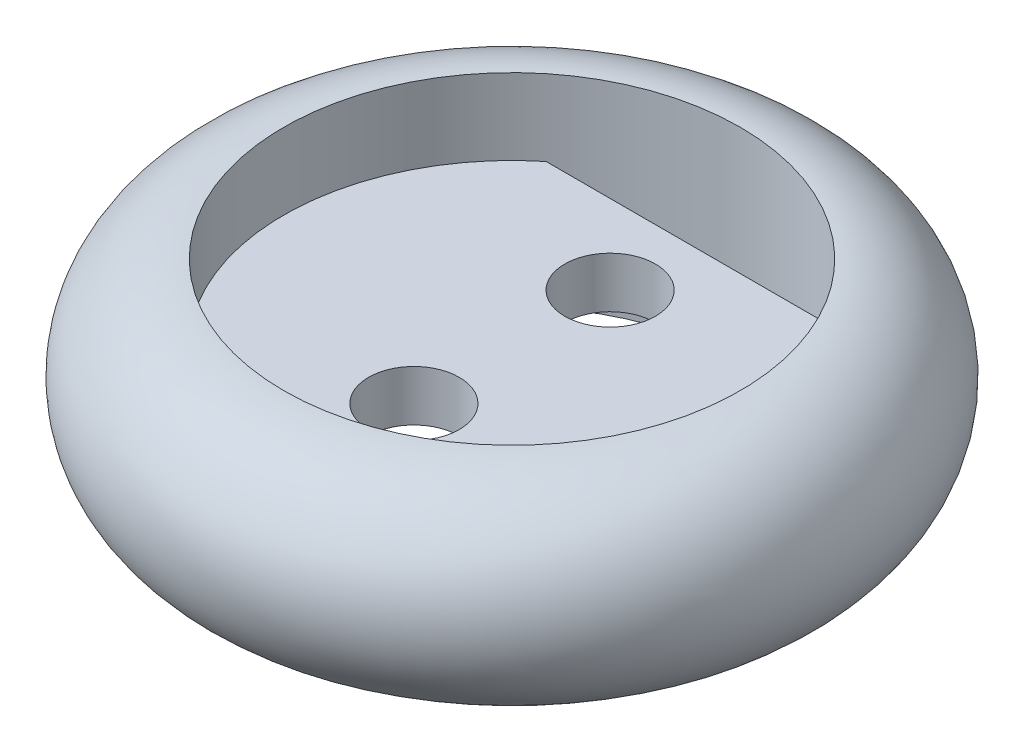
SolidWorks part; units mm, degrees
ref_plane "前视基准面" through (0, 0, 0) normal (0, 0, 1) x (1, 0, 0)
ref_plane "上视基准面" through (0, 0, 0) normal (0, 1, 0) x (1, 0, 0)
ref_plane "右视基准面" through (0, 0, 0) normal (1, 0, 0) x (0, 0, -1)
other "Configuration Table"
sketch "草图1" plane through (0, 0, 0) normal (0, 1, 0) x (1, 0, 0)
  line L1 (-45, 35) -> (45, 35)
  line L2 (-45, 35) -> (-45, -35)
  line L3 (-45, -35) -> (45, -35)
  line L4 (45, 35) -> (45, -35)
  line L5 (-45, 35) -> (45, -35) construction
  line L6 (-45, -35) -> (45, 35) construction
  point P0 (0, 0)
  dimension "D1" = 90
  dimension "D2" = 70
extrude "凸台-拉伸1" add sketch "草图1" along normal blind 10
fillet "圆角1" radius 10 4 edges at (-45, 5, -35) (45, 5, -35) (45, 5, 35) (-45, 5, 35)
sketch "草图2" plane through (0, 10, 0) normal (0, 1, 0) x (1, 0, 0)
  line L0 (-28.9454, 0) -> (25.4719, 0) construction
  circle A0 centre (0, 19.3452) radius 8.9356
  circle A1 centre (0, -19.3452) radius 8.9356
extrude "切除-拉伸1" cut sketch "草图2" against normal blind 10
sketch "草图5" plane through (0, 0, 0) normal (0, 0, 1) x (1, 0, 0)
  line L0 (45, 10) -> (45, 0) construction
  line L1 (45, 25) -> (45, -15)
  line L2 (0, 30.8338) -> (0, -21.6006) construction
  arc A0 (45, -15) -> (45, 25) centre (45, 5) ccw
  dimension "D1" = 40
revolve "旋转1" add sketch "草图5" angle 360 about L2
